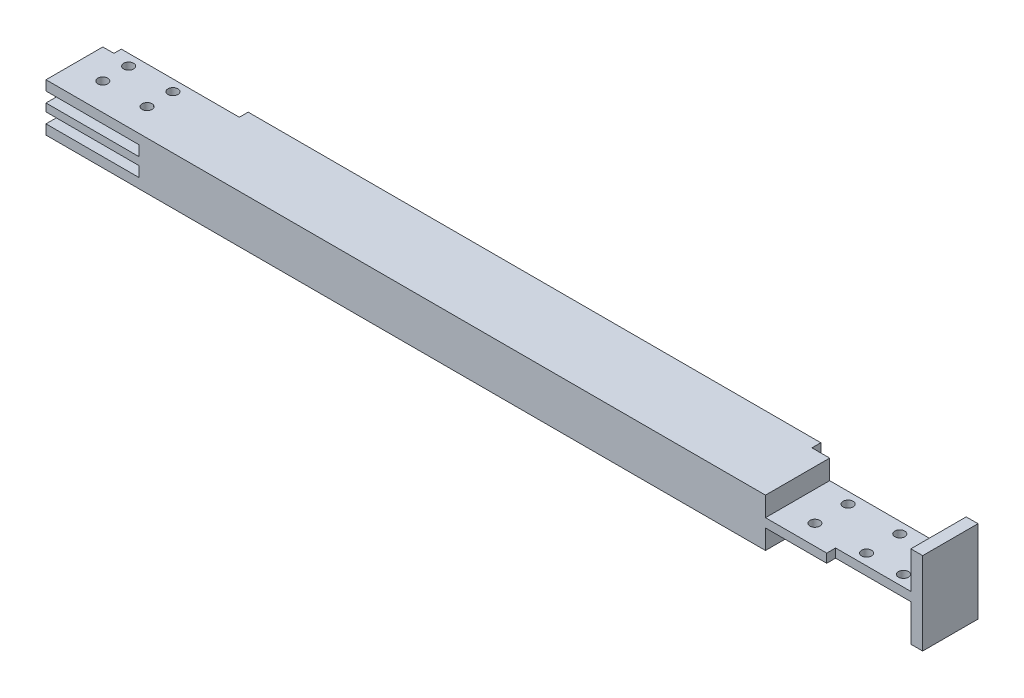
SolidWorks part; units mm, degrees
ref_plane "Front Plane" through (0, 0, 0) normal (0, 0, 1) x (1, 0, 0)
ref_plane "Top Plane" through (0, 0, 0) normal (0, 1, 0) x (1, 0, 0)
ref_plane "Right Plane" through (0, 0, 0) normal (1, 0, 0) x (0, 0, -1)
sketch "Sketch1" plane through (0, 0, 0) normal (0, 1, 0) x (1, 0, 0)
  line L6 (-588, 37.5) -> (588, 37.5)
  line L11 (-588, 37.5) -> (-588, -37.5)
  line L12 (-588, -37.5) -> (588, -37.5)
  line L13 (588, 37.5) -> (588, -37.5)
  line L14 (-588, 37.5) -> (588, -37.5) construction
  line L15 (-588, -37.5) -> (588, 37.5) construction
  point P0 (0, 0)
  dimension "D1" = 1176
  dimension "D2" = 75
extrude "Boss-Extrude1" add sketch "Sketch1" along normal blind 65
sketch "Sketch2" plane through (0, 0, -37.5) normal (0, 0, 1) x (1, 0, 0)
  line L0 (-588, 65) -> (588, 65) construction
  line L1 (-413, 65) -> (363, 65)
  line L2 (-413, 65) -> (-413, 0)
  line L3 (-413, 0) -> (363, 0)
  line L4 (363, 65) -> (363, 0)
  line L5 (-588, 0) -> (588, 0) construction
  line L6 (-588, 65) -> (-588, 0) construction
  dimension "D1" = 776
  dimension "D2" = 175
extrude "Boss-Extrude2" add sketch "Sketch2" against normal blind 12
sketch "Sketch3" plane through (0, 0, 37.5) normal (0, 0, 1) x (1, 0, 0)
  line L0 (-588, 0) -> (588, 0) construction
  line L1 (-588, 65) -> (470, 65)
  line L2 (-588, 65) -> (-588, 0)
  line L3 (-588, 0) -> (470, 0)
  line L4 (470, 65) -> (470, 0)
  dimension "D1" = 1058
extrude "Boss-Extrude3" add sketch "Sketch3" along normal blind 12
sketch "Sketch4" plane through (0, 0, 37.5) normal (0, 0, 1) x (1, 0, 0)
  line L0 (588, 65) -> (588, 0) construction
  line L9 (588, -23.5) -> (572, -23.5)
  line L10 (588, -23.5) -> (588, 88.5)
  line L11 (588, 88.5) -> (572, 88.5)
  line L12 (572, -23.5) -> (572, 88.5)
  point P0 (588, 32.5)
  point P3 (588, 32.5)
  line M13 (470, 0) -> (588, 0)
  line M14 (588, 0) -> (588, 65)
  line M15 (588, 65) -> (470, 65)
  dimension "D1" = 112
  dimension "D2" = 16
extrude "Boss-Extrude4" add sketch "Sketch4" against normal up to surface (75 mm away) contours L12 L9 L10 M13 | L12 M13 M14 M15 | L12 L10 L11 M15 up to face at (475.5, 32.5, -37.5)
sketch "Sketch5" plane through (0, 0, 37.5) normal (0, 0, 1) x (1, 0, 0)
  line L0 (470, 0) -> (470, 65) construction
  line L1 (572, -23.5) -> (470, -23.5)
  line L2 (572, -23.5) -> (572, 26.5)
  line L3 (572, 26.5) -> (470, 26.5)
  line L4 (470, -23.5) -> (470, 26.5)
  line L5 (470, 0) -> (470, 65) construction
  line L6 (572, 88.5) -> (470, 88.5)
  line L7 (572, 88.5) -> (572, 38.5)
  line L8 (572, 38.5) -> (470, 38.5)
  line L9 (470, 88.5) -> (470, 38.5)
  dimension "D1" = 50
  dimension "D2" = 50
extrude "Cut-Extrude1" cut sketch "Sketch5" against normal through all both and the other way through all
hole_wizard "Ø12.0mm Dowel Hole1" positions "Sketch6" profile "Sketch7" hole size "Ø12.0" standard "ISO" end condition up to next
sketch "Sketch6" plane through (0, 65, 0) normal (0, 1, 0) x (1, 0, 0)
  line L0 (470, -49.5) -> (-588, -49.5) construction
  line L1 (-588, 37.5) -> (-588, -49.5) construction
  line L2 (-413, 37.5) -> (-588, 37.5) construction
  line L3 (588, 37.5) -> (588, -37.5) construction
  line L5 (470, 37.5) -> (572, 37.5) construction
  line L6 (572, -37.5) -> (470, -37.5) construction
  point P7 (-548, -12.5)
  point P9 (-488, -12.5)
  point P11 (-488, 22.5)
  point P13 (-548, 22.5)
  point P24 (427, 22.5)
  point P26 (497, 22.5)
  point P28 (547, 22.5)
  point P30 (547, -22.5)
  point P32 (497, -22.5)
  point P34 (427, -22.5)
  dimension "D1" = 37
  dimension "D2" = 35
  dimension "D3" = 40
  dimension "D4" = 60
  dimension "D5" = 15
  dimension "D6" = 41
  dimension "D7" = 50
  dimension "D8" = 70
  dimension "D9" = 45
  dimension "D10" = 15
  dimension "D11" = 15
sketch "Sketch7" plane through (-548, 65, 12.5) normal (1, 0, 0) x (0, 0, 1)
  line L0 (0, 0) -> (0, 65)
  line L1 (0, 65) -> (6.75, 65)
  line L2 (6.75, 65) -> (6.75, 0)
  line L5 (6.75, 0) -> (0, 0)
  line L11 (0, -6.35) -> (0, 107.95) construction
  dimension "Thru Hole Dia." = 13.5
  dimension "Thru Hole Depth" = 65
sketch "Sketch9" plane through (0, 0, -37.5) normal (0, 0, -1) x (-1, 0, 0)
  line L12 (462, 51.75) -> (462, 37.75)
  line L13 (462, 37.75) -> (600.4723, 37.75)
  line L14 (600.4723, 27.25) -> (462, 27.25)
  line L15 (462, 27.25) -> (462, 13.25)
  line L16 (462, 13.25) -> (569.203, 13.25)
  line L17 (569.203, 51.75) -> (462, 51.75)
  line L18 (462, 51.75) -> (462, 37.75)
  line L19 (462, 37.75) -> (600.4723, 37.75)
  line L20 (600.4723, 27.25) -> (462, 27.25)
  line L21 (462, 27.25) -> (462, 13.25)
  line L22 (462, 13.25) -> (569.203, 13.25)
  line L23 (569.203, 51.75) -> (462, 51.75)
  arc A4 (600.4723, 37.75) -> (600.4723, 27.25) centre (663.2532, 32.5) ccw
  arc A5 (569.203, 13.25) -> (569.203, 51.75) centre (663.2532, 32.5) ccw
  arc A6 (600.4723, 37.75) -> (600.4723, 27.25) centre (663.2532, 32.5) ccw
  arc A7 (569.203, 13.25) -> (569.203, 51.75) centre (663.2532, 32.5) ccw
  dimension "D1" = 1
extrude "Cut-Extrude2" cut sketch "Sketch9" against normal blind 10
sketch "Sketch11" plane through (0, 0, -37.5) normal (0, 0, -1) x (-1, 0, 0)
  line L1 (462, 51.75) -> (589.4909, 51.75)
  line L2 (462, 51.75) -> (462, 37.75)
  line L3 (462, 37.75) -> (589.4909, 37.75)
  line L4 (589.4909, 51.75) -> (589.4909, 37.75)
  line L5 (462, 13.25) -> (589.4909, 13.25)
  line L6 (462, 13.25) -> (462, 27.25)
  line L7 (462, 27.25) -> (589.4909, 27.25)
  line L8 (589.4909, 13.25) -> (589.4909, 27.25)
extrude "Cut-Extrude3" cut sketch "Sketch11" against normal through all both and the other way through all
sketch "Sketch12" plane through (0, 0, -37.5) normal (0, 0, -1) x (-1, 0, 0)
  line L1 (-470, 0) -> (-363, 0) construction
  line L2 (-470, 26.5) -> (-387, 26.5)
  line L3 (-470, 26.5) -> (-470, 0)
  line L4 (-470, 0) -> (-387, 0)
  line L5 (-387, 26.5) -> (-387, 0)
  line L6 (-470, 65) -> (-363, 65) construction
  line L7 (-470, 38.5) -> (-387, 38.5)
  line L8 (-470, 38.5) -> (-470, 65)
  line L9 (-470, 65) -> (-387, 65)
  line L10 (-387, 38.5) -> (-387, 65)
extrude "Cut-Extrude4" cut sketch "Sketch12" against normal through all both
